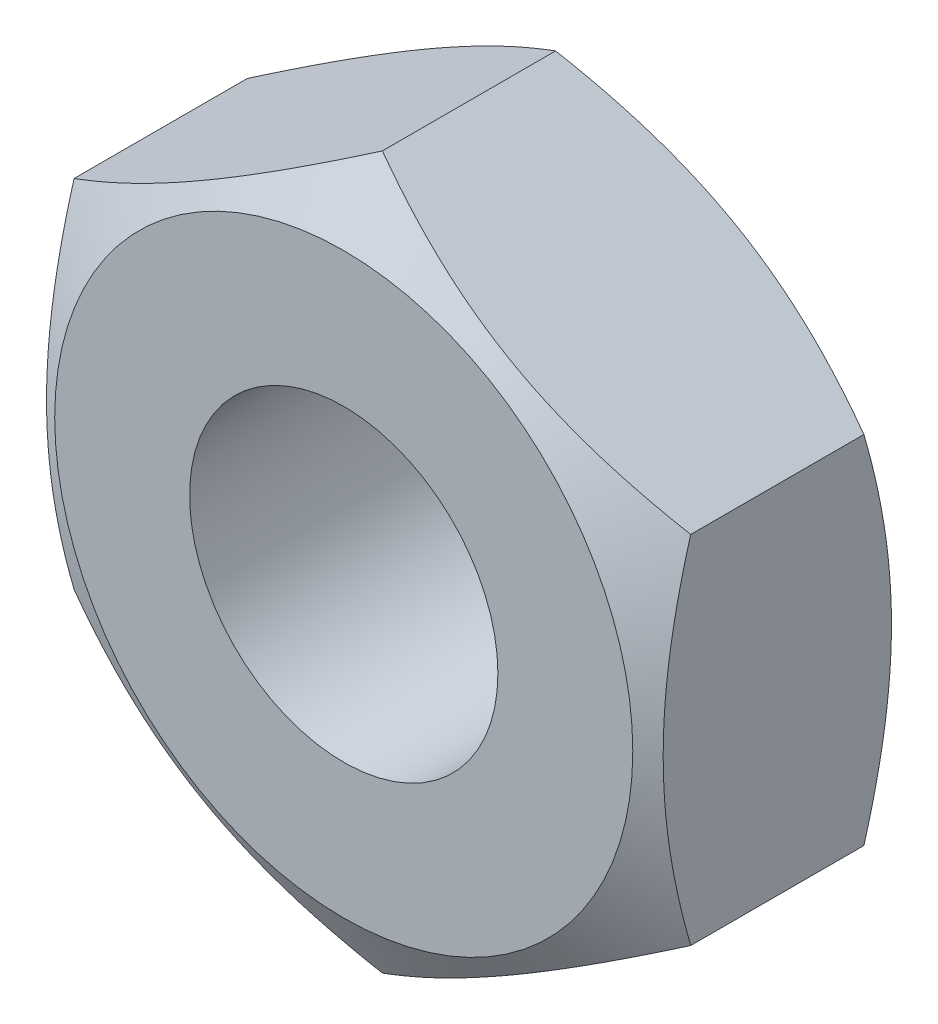
SolidWorks part; units mm, degrees
ref_plane "Front Plane" through (0, 0, 0) normal (0, 0, 1) x (1, 0, 0)
ref_plane "Top Plane" through (0, 0, 0) normal (0, 1, 0) x (1, 0, 0)
ref_plane "Right Plane" through (0, 0, 0) normal (1, 0, 0) x (0, 0, -1)
sketch "Sketch1" plane through (0, 0, 0) normal (0, 0, 1) x (1, 0, 0)
  line L1 (0, 1.8475) -> (-1.6, 0.9238)
  line L2 (-1.6, 0.9238) -> (-1.6, -0.9238)
  line L3 (-1.6, -0.9238) -> (0, -1.8475)
  line L4 (0, -1.8475) -> (1.6, -0.9238)
  line L5 (1.6, -0.9238) -> (1.6, 0.9238)
  line L6 (1.6, 0.9238) -> (0, 1.8475)
  circle A0 centre (0, 0) radius 1.6 construction
  circle A1 centre (0, 0) radius 0.8
  dimension "D1" = 1.6
  dimension "D2" = 3.2
extrude "Extrude1" add sketch "Sketch1" along normal blind 1.3
sketch "Sketch2" plane through (0, 0, 0) normal (0, 1, 0) x (1, 0, 0)
  line L0 (0, 0) -> (-1.5, 0)
  line L1 (-1.5, 0) -> (-2.6258, -0.65)
  line L2 (-3.1927, -1.3) -> (-3.1927, 0)
  line L3 (-3.1927, 0) -> (-1.5, 0)
  line L4 (0, 0) -> (0, 0.6494) construction
  line L5 (0, 0) -> (0, -1.3) construction
  line L6 (0, -0.65) -> (2.1666, -0.65) construction
  line L7 (-3.1927, -1.3) -> (-1.5, -1.3)
  line L8 (-1.5, -1.3) -> (-2.6258, -0.65)
  point P15 (-3.1927, -0.65)
revolve "Cut-Revolve1" cut sketch "Sketch2" angle 360 about L4
